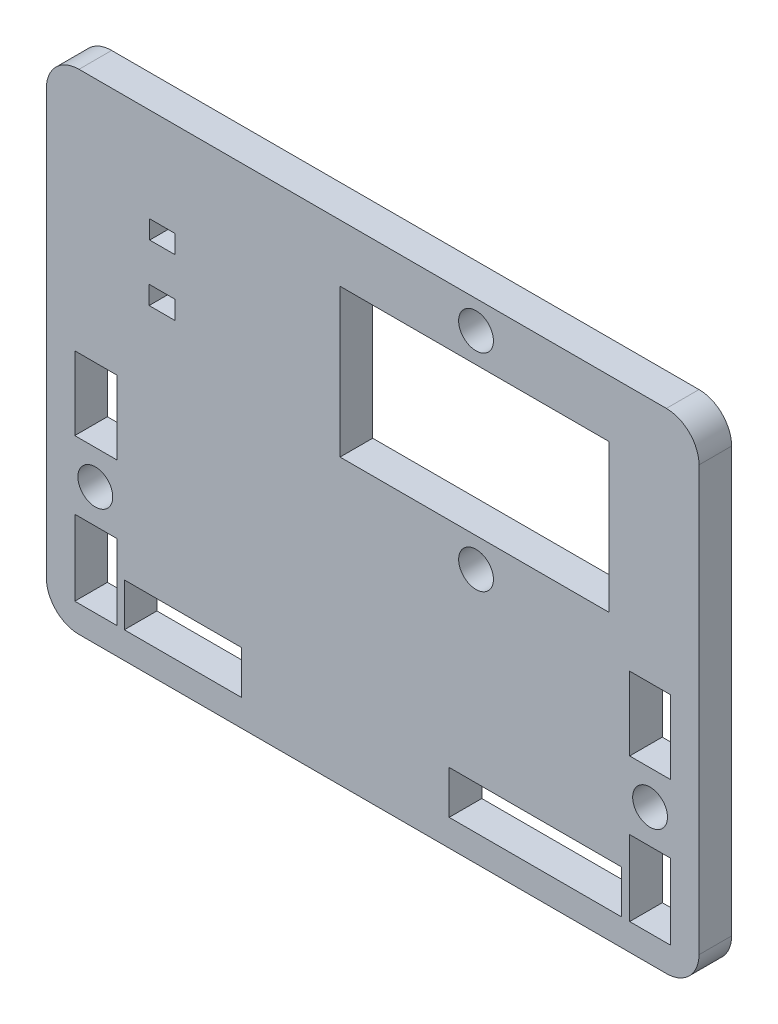
SolidWorks part; units mm, degrees
ref_plane "前视基准面" through (0, 0, 0) normal (0, 0, 1) x (1, 0, 0)
ref_plane "上视基准面" through (0, 0, 0) normal (0, 1, 0) x (1, 0, 0)
ref_plane "右视基准面" through (0, 0, 0) normal (1, 0, 0) x (0, 0, -1)
ref_plane "基准面4" through (0, 0, 0) normal (0, 0, -1) x (-1, 0, 0)
sketch "草图1" plane through (0, 0, 0) normal (0, 0, -1) x (-1, 0, 0)
  line L0 (21.7688, 6.4282) -> (21.7688, 2.4523)
  line L1 (21.7688, 2.4523) -> (10.9838, 2.4523)
  line L2 (10.9838, 2.4523) -> (10.9838, 6.4282)
  line L3 (10.9838, 6.4282) -> (21.7688, 6.4282)
  line L4 (26.3232, 9.3787) -> (26.3232, 2.4523)
  line L5 (26.3232, 2.4523) -> (22.442, 2.4523)
  line L6 (22.442, 2.4523) -> (22.442, 9.3787)
  line L7 (22.442, 9.3787) -> (26.3232, 9.3787)
  line L8 (26.3232, 22.3918) -> (26.3232, 15.6378)
  line L9 (26.3232, 15.6378) -> (22.442, 15.6378)
  line L10 (22.442, 15.6378) -> (22.442, 22.3918)
  line L11 (22.442, 22.3918) -> (26.3232, 22.3918)
  line L12 (19.4892, 31.104) -> (19.4892, 29.41)
  line L13 (19.4892, 29.41) -> (17.1082, 29.41)
  line L14 (17.1082, 29.41) -> (17.1082, 31.104)
  line L15 (17.1082, 31.104) -> (19.4892, 31.104)
  line L16 (19.4352, 36.343) -> (19.4352, 34.65)
  line L17 (19.4352, 34.65) -> (17.1082, 34.65)
  line L18 (17.1082, 34.65) -> (17.1082, 36.343)
  line L19 (17.1082, 36.343) -> (19.4352, 36.343)
  line L20 (1.9325, 39.7241) -> (1.9325, 26.1237)
  line L21 (1.9325, 26.1237) -> (-22.8046, 26.1237)
  line L22 (-22.8046, 26.1237) -> (-22.8046, 39.7241)
  line L23 (-22.8046, 39.7241) -> (1.9325, 39.7241)
  line L24 (-8.0982, 6.4282) -> (-8.0982, 2.4523)
  line L25 (-8.0982, 2.4523) -> (-23.9328, 2.4523)
  line L26 (-23.9328, 2.4523) -> (-23.9328, 6.4282)
  line L27 (-23.9328, 6.4282) -> (-8.0982, 6.4282)
  line L28 (-24.692, 9.3787) -> (-24.692, 2.4523)
  line L29 (-24.692, 2.4523) -> (-28.4275, 2.4523)
  line L30 (-28.4275, 2.4523) -> (-28.4275, 9.3787)
  line L31 (-28.4275, 9.3787) -> (-24.692, 9.3787)
  line L32 (28.9332, 3) -> (28.9332, 41.999)
  line L33 (25.9332, 44.999) -> (-28.0668, 44.999)
  line L34 (-31.0668, 41.999) -> (-31.0668, 3)
  line L35 (-28.0668, 0) -> (25.9332, 0)
  line L36 (-24.692, 22.3918) -> (-24.692, 15.6378)
  line L37 (-24.692, 15.6378) -> (-28.4275, 15.6378)
  line L38 (-28.4275, 15.6378) -> (-28.4275, 22.3918)
  line L39 (-28.4275, 22.3918) -> (-24.692, 22.3918)
  arc A0 (25.9332, 0) -> (28.9332, 3) centre (25.9332, 3) ccw
  arc A1 (28.9332, 41.999) -> (25.9332, 44.999) centre (25.9332, 41.999) ccw
  arc A2 (-28.0668, 44.999) -> (-31.0668, 41.999) centre (-28.0668, 41.999) ccw
  arc A3 (-31.0668, 3) -> (-28.0668, 0) centre (-28.0668, 3) ccw
  circle A4 centre (-26.5678, 12.499) radius 1.35
  circle A5 centre (-10.5678, 23.43) radius 1.6
  circle A6 centre (24.4322, 12.499) radius 1.35
  circle A7 centre (-10.5678, 42.43) radius 1.6
  dimension "D1" = 2.7
  dimension "D2" = 19
extrude "凸台-拉伸1" add sketch "草图1" against normal blind 3
sketch "草图2" plane through (0, 0, 3) normal (0, 0, 1) x (1, 0, 0)
  circle A0 centre (-24.4322, 12.499) radius 1.6
  circle A1 centre (26.5678, 12.499) radius 1.6
  dimension "D1" = 3.2
extrude "切除-拉伸1" cut sketch "草图2" against normal through all
